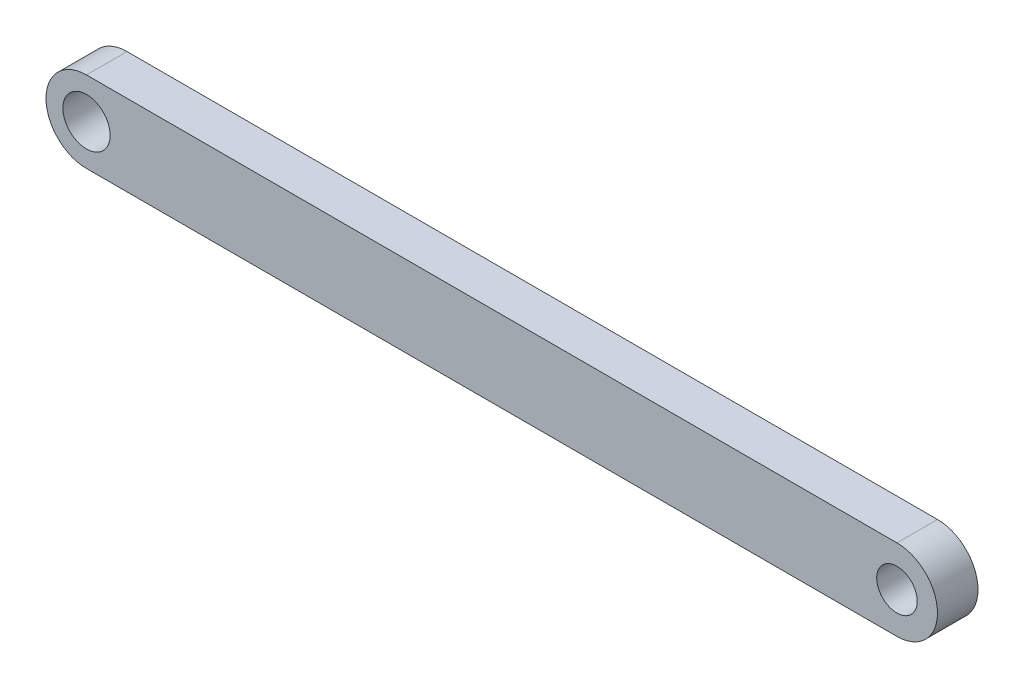
SolidWorks part; units mm, degrees
ref_plane "Front Plane" through (0, 0, 0) normal (0, 0, 1) x (1, 0, 0)
ref_plane "Top Plane" through (0, 0, 0) normal (0, 1, 0) x (1, 0, 0)
ref_plane "Right Plane" through (0, 0, 0) normal (1, 0, 0) x (0, 0, -1)
sketch "Sketch1" plane through (0, 0, 0) normal (0, 0, 1) x (1, 0, 0)
  line L0 (0, 0) -> (60, 0) construction
  line L1 (0, 3) -> (60, 3)
  line L2 (0, -3) -> (60, -3)
  arc A0 (0, 3) -> (0, -3) centre (0, 0) ccw
  arc A1 (60, -3) -> (60, 3) centre (60, 0) ccw
  circle A2 centre (0, 0) radius 1.75
  circle A3 centre (60, 0) radius 1.5
  point P3 (30, 0)
  dimension "D2" = 3.5
  dimension "D3" = 3
  dimension "D1" = 60
  dimension "D4" = 6
extrude "Boss-Extrude1" add sketch "Sketch1" along normal blind 3 contours L1 A1 L2 A0
